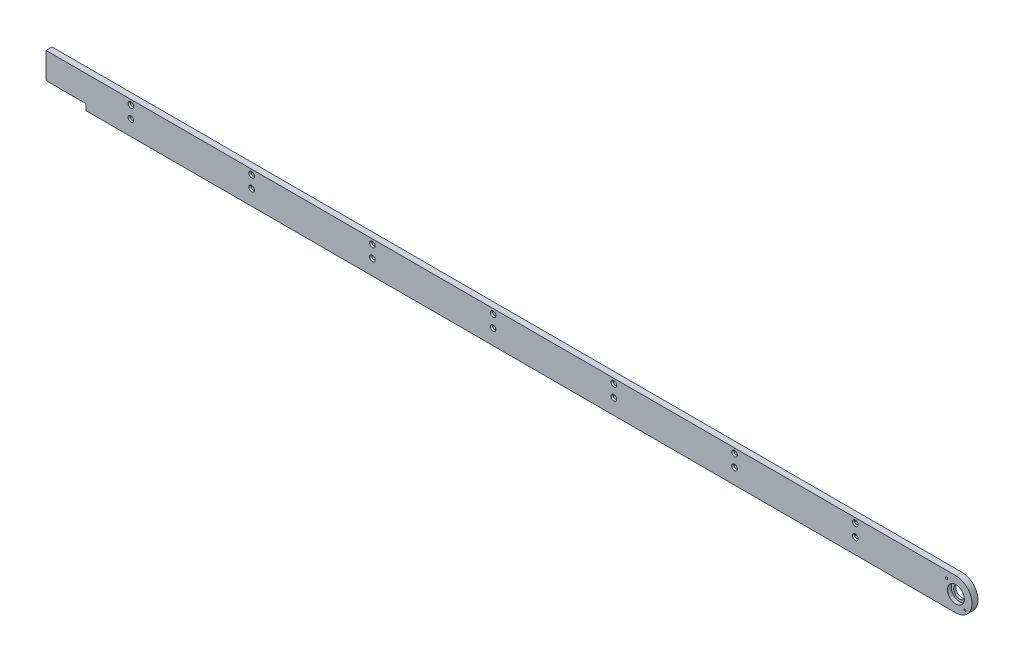
SolidWorks part; units mm, degrees
material "3.3549 (EN-AW 5182)"
ref_plane "Piano frontale" through (0, 0, 0) normal (0, 0, 1) x (1, 0, 0)
ref_plane "Piano superiore" through (0, 0, 0) normal (0, 1, 0) x (1, 0, 0)
ref_plane "Piano destro" through (0, 0, 0) normal (1, 0, 0) x (0, 0, -1)
sketch "Schizzo1" plane through (0, 0, 0) normal (0, 0, 1) x (1, 0, 0)
  line L0 (-1150, 0) -> (1150, 0) construction
  line L1 (-1150, 40) -> (1150, 40)
  line L2 (0, 40) -> (0, -40) construction
  line L3 (-1150, -40) -> (1150, -40)
  arc A0 (-1150, 40) -> (-1150, -40) centre (-1150, 0) ccw
  arc A1 (1150, 40) -> (1150, -40) centre (1150, 0) cw
  dimension "D1" = 2300
  dimension "D2" = 80
extrude "Estrusione1" add sketch "Schizzo1" along normal blind 15
sketch "Schizzo2" plane through (0, 0, 15) normal (0, 0, 1) x (1, 0, 0)
  line L0 (0, 77.3851) -> (0, -78.0058) construction
  circle A0 centre (-1150, 0) radius 4
  circle A1 centre (1150, 0) radius 15
  dimension "D1" = 8
  dimension "D2" = 30
extrude "Taglio-Estrusione1" cut sketch "Schizzo2" against normal blind 15
sketch "Schizzo3" plane through (0, 0, 15) normal (0, 0, 1) x (1, 0, 0)
  line L0 (1150, 40) -> (-1150, 40) construction
  line L1 (-1111, 40) -> (951, 40)
  line L2 (-1111, 40) -> (-1111, 10)
  line L3 (-1111, 10) -> (948, 10)
  line L4 (951, 40) -> (951, 13)
  arc A1 (951, 13) -> (948, 10) centre (948, 13) cw
  arc A2 (-1150, 40) -> (-1150, -40) centre (-1150, 0) ccw construction
  arc A3 (1150, -40) -> (1150, 40) centre (1150, 0) ccw construction
  dimension "D4" = 30
  dimension "D2" = 199
  dimension "D1" = 39
extrude "Taglio-Estrusione2" [suppressed] cut sketch "Schizzo3" against normal blind 20
sketch "Schizzo4" plane through (0, 0, 15) normal (0, 0, 1) x (1, 0, 0)
  circle A0 centre (-1150, 0) radius 6.75
  dimension "D1" = 13.5
extrude "Taglio-Estrusione3" cut sketch "Schizzo4" against normal blind 8.5
sketch "Schizzo5" plane through (0, 0, 15) normal (0, 0, 1) x (1, 0, 0)
  line L0 (-1248.0058, -2) -> (1254.694, -2) construction
  line L1 (-1248.0058, 28) -> (1254.694, 28) construction
  line L2 (-1150, -40) -> (1150, -40) construction
  line L3 (0, 76.173) -> (0, -76.173) construction
  circle A1 centre (0, -2) radius 4
  circle A2 centre (0, 28) radius 4
  dimension "D4" = 8
  dimension "D5" = 8
  dimension "D1" = 30
  dimension "D2" = 38
extrude "Taglio-Estrusione4" cut sketch "Schizzo5" against normal blind 30
chamfer "Smusso1" distance 3 angle 45 2 edges at (4, -2, 15) (4, 28, 15)
sketch "Schizzo11" plane through (0, 0, 15) normal (0, 0, 1) x (1, 0, 0)
  line L0 (-1150, -40) -> (1150, -40) construction
  line L1 (-1150, 40) -> (-1111, 40)
  line L3 (-1150, -40) -> (-1011, -40)
  line L4 (-1111, 40) -> (-1111, -20)
  line L5 (-1106, -25) -> (-1016, -25)
  line L8 (-1011, -30) -> (-1011, -40)
  line L10 (1150, 40) -> (-1150, 40) construction
  circle A0 centre (-1150, 0) radius 4 construction
  arc A1 (-1150, 40) -> (-1150, -40) centre (-1150, 0) ccw construction
  arc A2 (-1150, 40) -> (-1150, -40) centre (-1150, 0) ccw
  arc A3 (-1106, -25) -> (-1111, -20) centre (-1106, -20) cw
  arc A4 (-1016, -25) -> (-1011, -30) centre (-1016, -30) cw
  dimension "D1" = 139
  dimension "D3" = 5
  dimension "D2" = 15
  dimension "D4" = 39
extrude "Taglio-Estrusione8" cut sketch "Schizzo11" against normal blind 30
sketch "Schizzo12" plane through (0, -25, 0) normal (0, -1, 0) x (1, 0, 0)
  line L0 (-1213.2687, 7.5) -> (-959.655, 7.5) construction
  line L1 (-1016, 0) -> (-1106, 0) construction
  line L2 (-1111, 0) -> (-1111, 15) construction
  circle A0 centre (-1095, 7.5) radius 4
  circle A1 centre (-1045, 7.5) radius 4
  dimension "D3" = 8
  dimension "D5" = 8
  dimension "D1" = 7.5
  dimension "D2" = 16
  dimension "D4" = 50
extrude "Taglio-Estrusione9" cut sketch "Schizzo12" against normal blind 30
sketch "Schizzo13" plane through (0, 0, 15) normal (0, 0, 1) x (1, 0, 0)
  circle A0 centre (1150, 0) radius 21
  dimension "D1" = 42
extrude "Taglio-Estrusione10" cut sketch "Schizzo13" against normal blind 9.5
pattern_linear "Ripetizione a L1" count 4 spacing 300 along (-1, 0, 0) count 4 spacing 300 along (1, 0, 0) of "Taglio-Estrusione4", "Smusso1"
hole_wizard "Foro filettato M6-1" positions "Schizzo15" profile "Schizzo16" tap size "M6" standard "ISO" end condition through all
sketch "Schizzo15" plane through (0, 0, 15) normal (0, 0, 1) x (1, 0, 0)
  line L0 (1105.5386, 0) -> (1197.2996, 0) construction
  line L1 (1127.019, 22.981) -> (1172.981, -22.981) construction
  circle A0 centre (1150, 0) radius 32.5 construction
  point P0 (1127.019, 22.981)
  point P2 (1172.981, -22.981)
  dimension "D1" = 65
  dimension "D2" = 45
sketch "Schizzo16" plane through (1127.019, 22.981, 15) normal (1, 0, 0) x (0, -1, 0)
  line L0 (0, 0) -> (0, 15)
  line L1 (0, 15) -> (2.5, 15)
  line L2 (2.5, 15) -> (2.5, 0)
  line L5 (2.5, 0) -> (0, 0)
  line L11 (0, -6.35) -> (0, 107.95) construction
  dimension "Thru Tap Drill Dia." = 5
  dimension "Thru Tap Drill Depth" = 15
cosmetic thread "Filettatura del foro1" parameters "D2"=6
cosmetic thread "Filettatura del foro2" parameters "D2"=6
